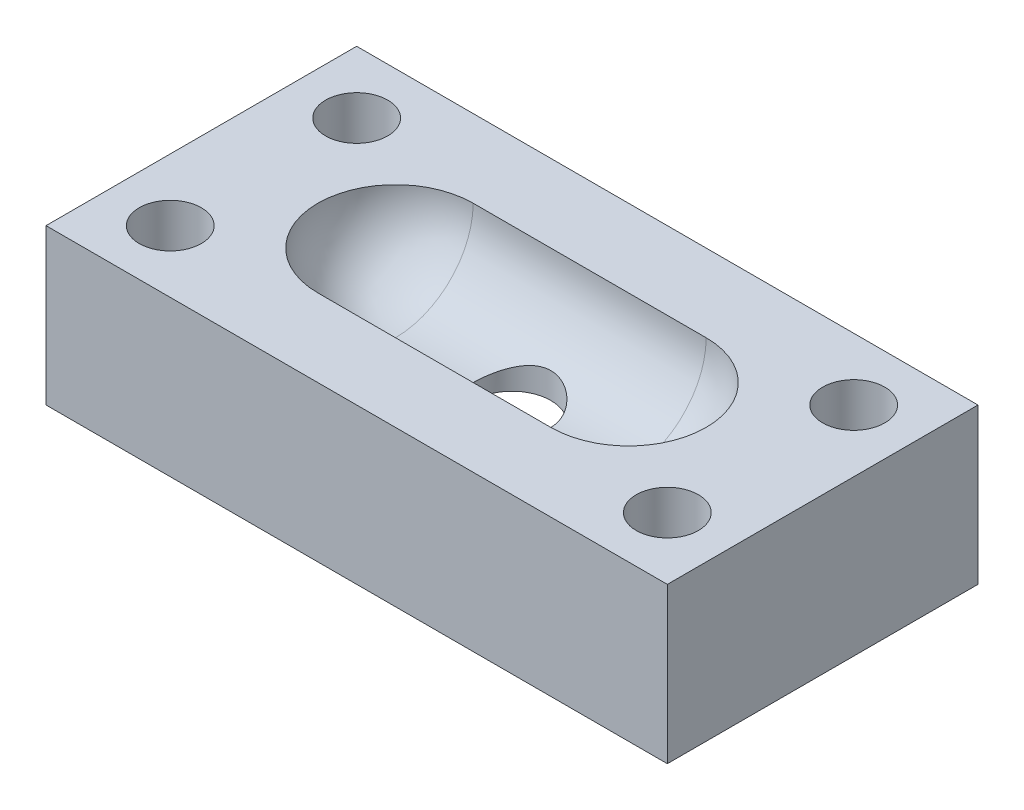
SolidWorks part; units mm, degrees
ref_plane "Front Plane" through (0, 0, 0) normal (0, 0, 1) x (1, 0, 0)
ref_plane "Top Plane" through (0, 0, 0) normal (0, 1, 0) x (1, 0, 0)
ref_plane "Right Plane" through (0, 0, 0) normal (1, 0, 0) x (0, 0, -1)
sketch "Sketch1" plane through (0, 0, 0) normal (0, 1, 0) x (1, 0, 0)
  line L0 (-16, -6) -> (-16, 6) construction
  line L1 (-20, -10) -> (20, -10)
  line L2 (-20, -10) -> (-20, 10)
  line L3 (-20, 10) -> (20, 10)
  line L4 (20, -10) -> (20, 10)
  line L5 (-20, -10) -> (20, 10) construction
  line L6 (-20, 10) -> (20, -10) construction
  line L7 (-16, 6) -> (16, 6) construction
  line L8 (16, -6) -> (16, 6) construction
  line L9 (-16, -6) -> (16, -6) construction
  circle A0 centre (-16, 6) radius 2
  circle A1 centre (16, 6) radius 2
  circle A2 centre (16, -6) radius 2
  circle A3 centre (-16, -6) radius 2
  circle A4 centre (0, 0) radius 2.5
  point P0 (0, 0)
  dimension "D4" = 4
  dimension "D5" = 5
  dimension "D1" = 40
  dimension "D2" = 20
  dimension "D3" = 4
extrude "Boss-Extrude1" add sketch "Sketch1" along normal mid plane 10
sketch "Sketch2" plane through (0, 0, 0) normal (0, 0, 1) x (1, 0, 0)
  line L0 (-12.5, 5) -> (12.5, 5)
  line L1 (20, 5) -> (-20, 5) construction
  line L2 (-7.5, 0) -> (7.5, 0)
  arc A0 (-12.5, 5) -> (-7.5, 0) centre (-7.5, 5) ccw
  arc A1 (7.5, 0) -> (12.5, 5) centre (7.5, 5) ccw
  point P7 (0, 0)
  point P9 (0, 0)
  point P10 (0, 0)
  point P11 (0, 0)
  dimension "D1" = 25
  dimension "D2" = 5
revolve "Cut-Revolve1" cut sketch "Sketch2" angle 360 about L0
chamfer "Chamfer1" distance 1 angle 45 4 edges at (16, -5, 8) (16, -5, -4) (-16, -5, -4) (-16, -5, 8)
sketch "Sketch3" plane through (0, -5, 0) normal (0, -1, 0) x (1, 0, 0)
  line L0 (-5.6077, 0) -> (5.6077, 0) construction
  line L1 (-5.6077, 7) -> (5.6077, 7)
  line L2 (-5.6077, -7) -> (5.6077, -7)
  line L3 (-20, 10) -> (20, 10) construction
  line L4 (10.8921, 4.8472) -> (14.6744, -1.704) construction
  line L5 (16.4602, -0.7972) -> (12.837, 5.4785) construction
  line L6 (11.6699, 3.5) -> (13.4019, 4.5) construction
  arc A0 (-5.6077, 7) -> (-5.6077, -7) centre (-5.6077, 0) ccw
  arc A1 (5.6077, -7) -> (5.6077, 7) centre (5.6077, 0) ccw
  circle A2 centre (16, 6) radius 3 construction
  point P2 (0, 0)
  point P18 (0, 0)
  point P19 (0, 0)
  point P20 (0, 0)
  dimension "D1" = 3
  dimension "D2" = 2
extrude "Cut-Extrude1" cut sketch "Sketch3" against normal blind 4
fillet "Fillet1" radius 2 4 edges at (0, -1, 7) (12.6077, -1, 0) (0, -1, -7) (-12.6077, -1, 0)
